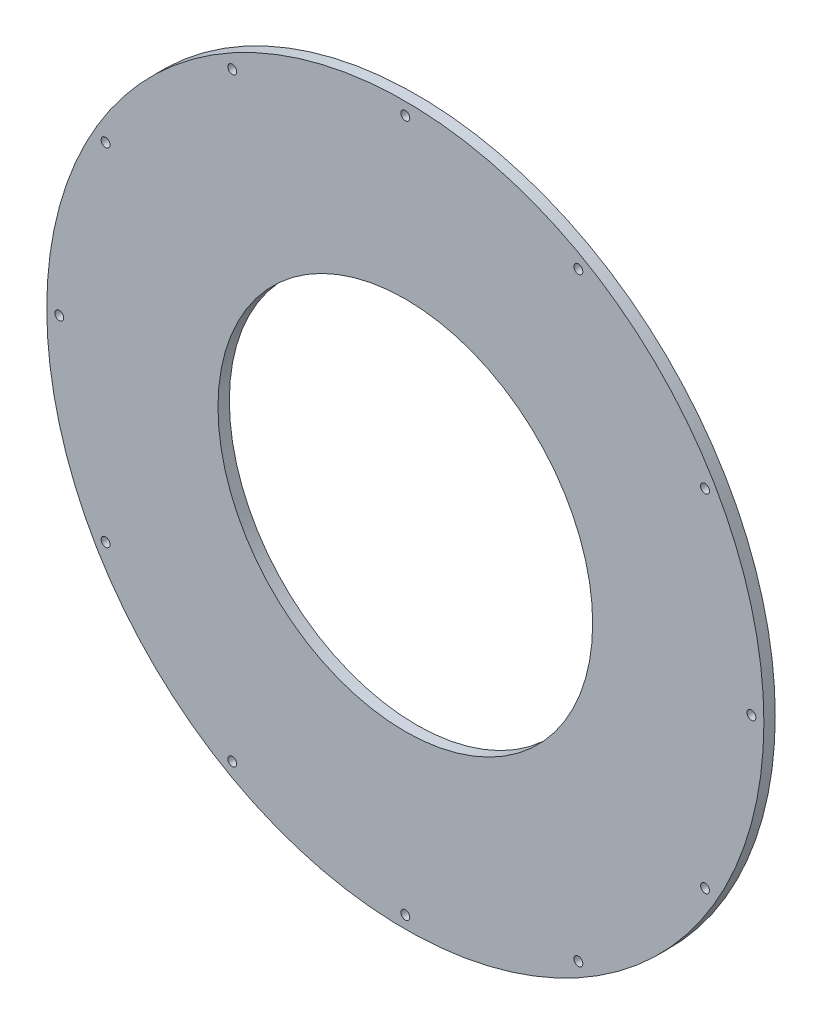
SolidWorks part; units mm, degrees
ref_plane "Front Plane" through (0, 0, 0) normal (1, 0, 0) x (0, 1, 0)
ref_plane "Top Plane" through (0, 0, 0) normal (0, 0, 1) x (0, 1, 0)
ref_plane "Right Plane" through (0, 0, 0) normal (0, 1, 0) x (-1, 0, 0)
sketch "Sketch1" plane through (0, 0, 0) normal (0, 0, 1) x (0, 1, 0)
  circle A0 centre (0, 0) radius 104.775
  circle A1 centre (0, 0) radius 200.533
  circle A2 centre (0, 0) radius 193.548 construction
  point P5 (-167.6175, 96.774)
  point P6 (0, 0)
  point P7 (0, 0)
  point P8 (0, 0)
  point P9 (-96.774, 167.6175)
  point P10 (0, 193.548)
  point P11 (96.774, 167.6175)
  point P12 (167.6175, 96.774)
  point P13 (193.548, 0)
  point P14 (167.6175, -96.774)
  point P15 (96.774, -167.6175)
  point P16 (0, -193.548)
  point P17 (-96.774, -167.6175)
  point P18 (-167.6175, -96.774)
  point P19 (-193.548, 0)
  point P20 (0, 0)
  dimension "D1" = 209.55
  dimension "D2" = 401.066
  dimension "D3" = 387.096
  dimension "D4" = 12
extrude "Boss-Extrude1" add sketch "Sketch1" along normal blind 6.35
sketch "Sketch2" plane through (0, 0, 6.35) normal (0, 0, 1) x (1, 0, 0)
  point P0 (-96.774, 167.6175)
  point P2 (-167.6175, 96.774)
  point P4 (-193.548, 0)
  point P6 (-167.6175, -96.774)
  point P8 (-96.774, -167.6175)
  point P10 (0, -193.548)
  point P12 (96.774, -167.6175)
  point P14 (167.6175, -96.774)
  point P16 (193.548, 0)
  point P18 (167.6175, 96.774)
  point P20 (96.774, 167.6175)
  point P22 (0, 193.548)
hole_wizard "#9 (0.196) Diameter Hole1" positions "Sketch2" profile "Sketch3" hole size "#9" standard "ANSI Inch" end condition through all
sketch "Sketch3" plane through (-96.774, 167.6175, 6.35) normal (1, 0, 0) x (0, -1, 0)
  line L0 (0, 0) -> (0, 6.35)
  line L1 (0, 6.35) -> (2.4892, 6.35)
  line L2 (2.4892, 6.35) -> (2.4892, 0)
  line L5 (2.4892, 0) -> (0, 0)
  line L11 (0, -6.35) -> (0, 107.95) construction
  dimension "Thru Hole Dia." = 4.9784
  dimension "Thru Hole Depth" = 6.35
